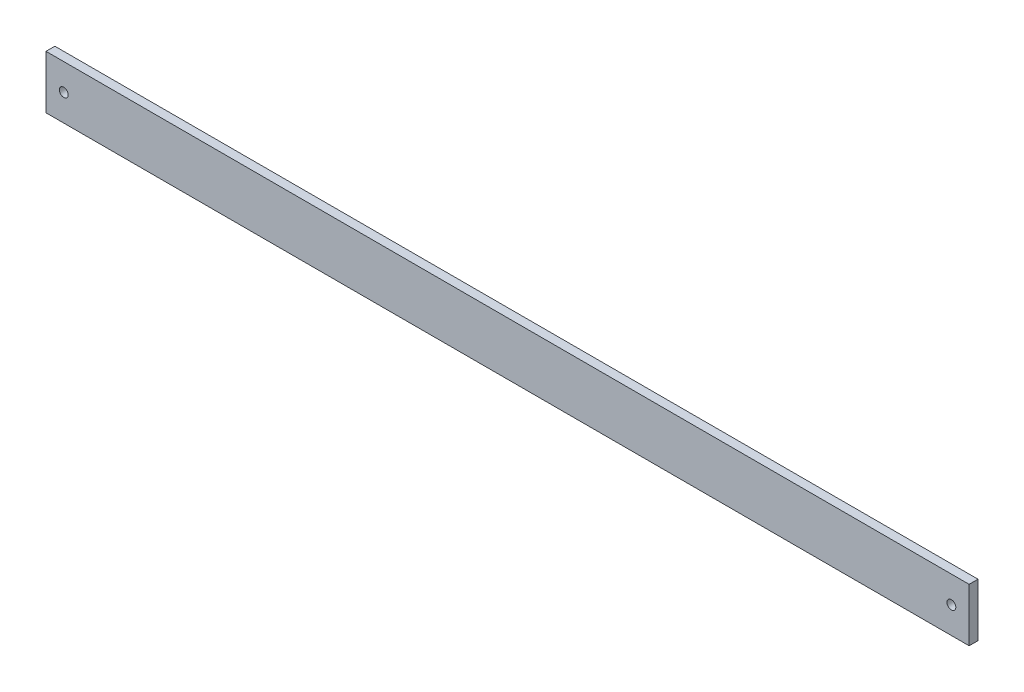
SolidWorks part; units mm, degrees
other "Markup1"
sketch "Sketch6" plane through (114.3, 38.1, 139.7) normal (0.0122, 0.8279, 0.5607) x (0.9984, -0.0412, 0.0392)
material "Balsa"
ref_plane "Front Plane" through (0, 0, 0) normal (0, 0, 1) x (1, 0, 0)
ref_plane "Top Plane" through (0, 0, 0) normal (0, 1, 0) x (1, 0, 0)
ref_plane "Right Plane" through (0, 0, 0) normal (1, 0, 0) x (0, 0, -1)
sketch "Sketch7" plane through (0, 0, 0) normal (0, 0, 1) x (1, 0, 0)
  line L1 (0, 0) -> (330.2, 0)
  line L2 (0, 0) -> (0, 19.05)
  line L3 (0, 19.05) -> (330.2, 19.05)
  line L4 (330.2, 0) -> (330.2, 19.05)
  circle A0 centre (6.35, 9.525) radius 1.5875
  circle A1 centre (323.85, 9.525) radius 1.5875
  dimension "Hole Diameter" = 3.175
  dimension "Hole Diameter2" = 3.175
  dimension "Width" = 19.05
  dimension "Total Length" = 330.2
  dimension "Hole Offset" = 6.35
  dimension "Length" = 317.5
extrude "Boss-Extrude1" add sketch "Sketch7" along normal blind 3.175
equation "\"Width@Sketch7\" = \"w\""
equation "\"L1\"= 15in"
equation "\"L2\"= 12.5in"
equation "\"L3\"= 15.207in"
equation "\"L4\"= 15in"
equation "\"LL\"= 30in"
equation "\"w\"= 0.75in"
equation "\"t\"= 0.125in"
equation "\"holeD\" = 0.125in"
equation "\"holeOffset\" = 0.25in"
equation "\"Total Length@Sketch7\" = \"L\" + 2 * \"holeOffset\""
equation "\"L\"= \"L2\""
equation "\"Hole Diameter@Sketch7\"= \"holeD\""
equation "\"Hole Diameter2@Sketch7\"= \"Hole Diameter@Sketch7\""
equation "\"Hole Offset@Sketch7\"= \"holeOffset\""
equation "\"Length@Sketch7\"= \"L\""
equation "\"Thickness@Boss-Extrude1\"= \"t\""
